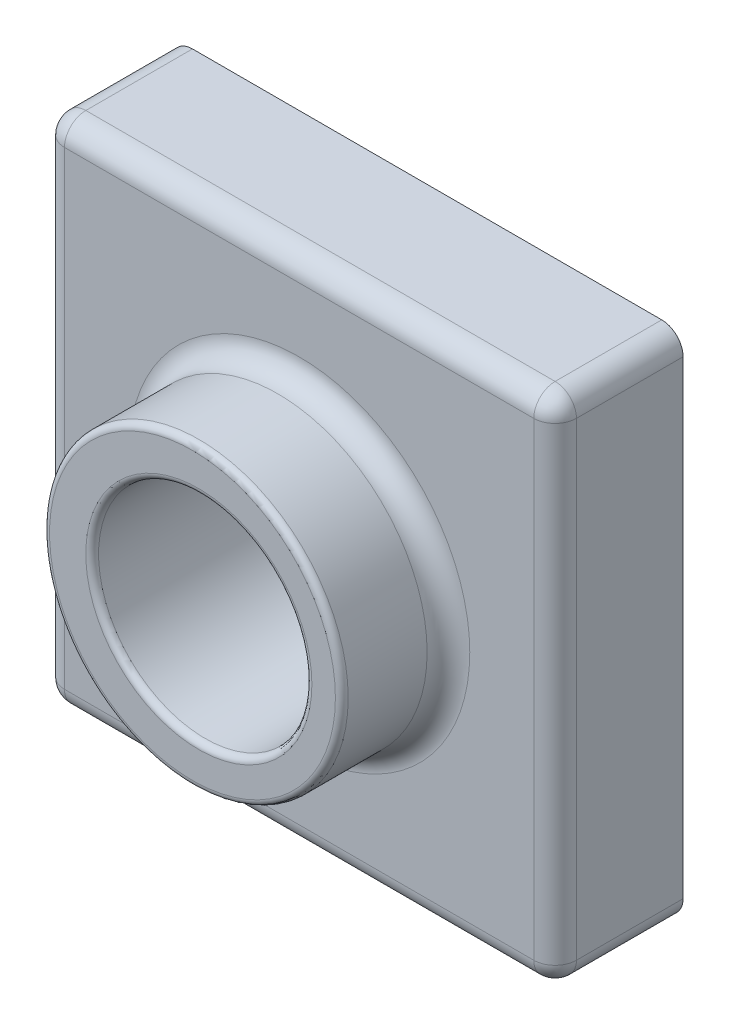
SolidWorks part; units mm, degrees
ref_plane "Plan de face" through (0, 0, 0) normal (0, 0, 1) x (1, 0, 0)
ref_plane "Plan de dessus" through (0, 0, 0) normal (0, 1, 0) x (1, 0, 0)
ref_plane "Plan de droite" through (0, 0, 0) normal (1, 0, 0) x (0, 0, -1)
sketch "Esquisse1" plane through (0, 0, 0) normal (0, 0, 1) x (1, 0, 0)
  line L1 (0, 0) -> (120, 0)
  line L2 (0, 0) -> (0, 120)
  line L3 (0, 120) -> (120, 120)
  line L4 (120, 0) -> (120, 120)
  dimension "D1" = 120
  dimension "D2" = 120
extrude "Boss.-Extru.1" add sketch "Esquisse1" along normal blind 30 contours L2 L1 L4 L3
sketch "Esquisse2" plane through (0, 0, 30) normal (0, 0, 1) x (1, 0, 0)
  circle A0 centre (60, 60) radius 35
extrude "Boss.-Extru.2" add sketch "Esquisse2" along normal blind 25 contours A0
sketch "Esquisse3" plane through (0, 0, 55) normal (0, 0, 1) x (1, 0, 0)
  circle A0 centre (61.4907, 60) radius 25
  dimension "D1" = 50
extrude "Enlèv. mat.-Extru.1" cut sketch "Esquisse3" against normal through all contours A0
fillet "Congé1" radius 5 9 edges at (120, 60, 30) (60, 0, 30) (0, 60, 30) (60, 120, 30) (95, 60, 30) (0, 0, 15) (0, 120, 15) (120, 0, 15) (120, 120, 15)
fillet "Congé2" radius 1.5 2 edges at (95, 60, 55) (86.4907, 60, 55)
shell "Coque1" thickness 2
